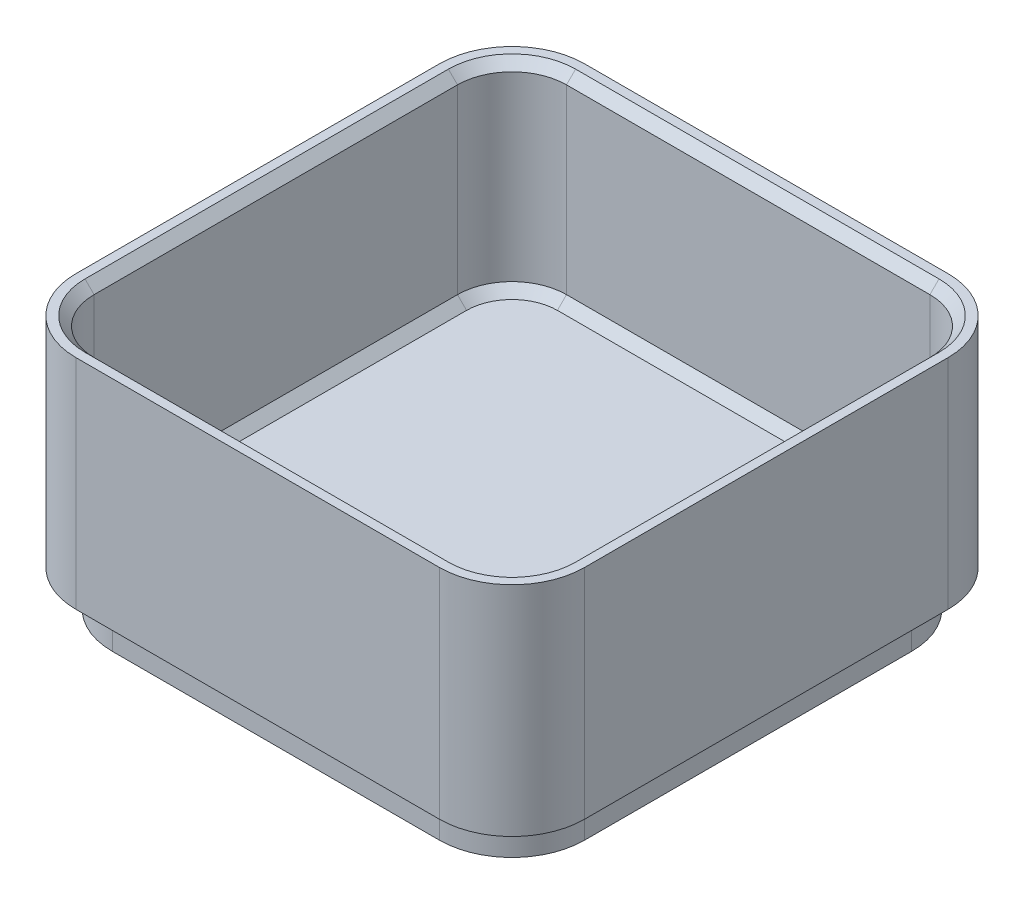
SolidWorks part; units mm, degrees
ref_plane "Front Plane" through (0, 0, 0) normal (0, 0, 1) x (1, 0, 0)
ref_plane "Top Plane" through (0, 0, 0) normal (0, 1, 0) x (1, 0, 0)
ref_plane "Right Plane" through (0, 0, 0) normal (1, 0, 0) x (0, 0, -1)
sketch "Sketch5" plane through (0, 0, 0) normal (0, 1, 0) x (1, 0, 0)
  line L1 (-22.5, -32.5) -> (22.5, -32.5)
  line L2 (-32.5, -22.5) -> (-32.5, 22.5)
  line L3 (-22.5, 32.5) -> (22.5, 32.5)
  line L4 (32.5, -22.5) -> (32.5, 22.5)
  line L5 (-32.5, -32.5) -> (32.5, 32.5) construction
  line L6 (-32.5, 32.5) -> (32.5, -32.5) construction
  arc A0 (-22.5, -32.5) -> (-32.5, -22.5) centre (-22.5, -22.5) cw
  arc A1 (22.5, -32.5) -> (32.5, -22.5) centre (22.5, -22.5) ccw
  arc A2 (22.5, 32.5) -> (32.5, 22.5) centre (22.5, 22.5) cw
  arc A3 (-32.5, 22.5) -> (-22.5, 32.5) centre (-22.5, 22.5) cw
  point P0 (0, 0)
  dimension "D3" = 10
  dimension "D1" = 65
  dimension "D2" = 65
extrude "Boss-Extrude4" add sketch "Sketch5" along normal blind 5
sketch "Sketch6" plane through (0, 5, 0) normal (0, 1, 0) x (1, 0, 0)
  line L1 (35, 35) -> (-35, 35)
  line L2 (35, 35) -> (35, -35)
  line L3 (35, -35) -> (-35, -35)
  line L4 (-35, 35) -> (-35, -35)
  line L5 (35, 35) -> (-35, -35) construction
  line L6 (35, -35) -> (-35, 35) construction
  point P0 (0, 0)
extrude "Boss-Extrude5" add sketch "Sketch6" along normal blind 30
sketch "Sketch8" plane through (0, 0, 0) normal (0, -1, 0) x (1, 0, 0)
  line L0 (-29.5711, 29.5711) -> (-22.5, 22.5)
  arc A0 (-22.5, 32.5) -> (-32.5, 22.5) centre (-22.5, 22.5) ccw construction
  circle A1 centre (-26.0355, 26.0355) radius 3
  circle A2 centre (26.0365, 26.0365) radius 3
  circle A3 centre (26.0375, -26.0355) radius 3
  circle A4 centre (-26.0345, -26.0365) radius 3
  point P8 (0, 0)
  point P15 (0.001, 0.001)
  point P18 (0.002, 0)
  point P21 (0.001, -0.001)
  point P22 (0.001, 0)
  dimension "D1" = 4
extrude "Cut-Extrude1" cut sketch "Sketch8" against normal blind 2 contours A3 | A2 | L0 A1 | L0 A1 | A4
fillet "Fillet1" radius 10 4 edges at (-35, 20, -35) (-35, 20, 35) (35, 20, 35) (35, 20, -35)
sketch "Sketch9" plane through (0, 35, 0) normal (0, 1, 0) x (1, 0, 0)
  line L8 (25, 32.5) -> (-25, 32.5)
  line L9 (-32.5, 25) -> (-32.5, -25)
  line L10 (-25, -32.5) -> (25, -32.5)
  line L11 (32.5, -25) -> (32.5, 25)
  line L12 (25, 32.5) -> (-25, 32.5)
  line L13 (-32.5, 25) -> (-32.5, -25)
  line L14 (-25, -32.5) -> (25, -32.5)
  line L15 (32.5, -25) -> (32.5, 25)
  arc A8 (-25, 32.5) -> (-32.5, 25) centre (-25, 25) ccw
  arc A9 (-32.5, -25) -> (-25, -32.5) centre (-25, -25) ccw
  arc A10 (25, -32.5) -> (32.5, -25) centre (25, -25) ccw
  arc A11 (32.5, 25) -> (25, 32.5) centre (25, 25) ccw
  arc A12 (-25, 32.5) -> (-32.5, 25) centre (-25, 25) ccw
  arc A13 (-32.5, -25) -> (-25, -32.5) centre (-25, -25) ccw
  arc A14 (25, -32.5) -> (32.5, -25) centre (25, -25) ccw
  arc A15 (32.5, 25) -> (25, 32.5) centre (25, 25) ccw
  dimension "D1" = 2.5
extrude "Cut-Extrude2" cut sketch "Sketch9" against normal blind 30
sketch "Sketch10" plane through (0, 5, 0) normal (0, -1, 0) x (1, 0, 0)
  line L8 (-35, 25) -> (-35, -25)
  line L9 (-25, -35) -> (25, -35)
  line L10 (35, -25) -> (35, 25)
  line L11 (25, 35) -> (-25, 35)
  line L12 (-35, 25) -> (-35, -25)
  line L13 (-25, -35) -> (25, -35)
  line L14 (35, -25) -> (35, 25)
  line L15 (25, 35) -> (-25, 35)
  arc A8 (-35, -25) -> (-25, -35) centre (-25, -25) ccw
  arc A9 (25, -35) -> (35, -25) centre (25, -25) ccw
  arc A10 (35, 25) -> (25, 35) centre (25, 25) ccw
  arc A11 (-25, 35) -> (-35, 25) centre (-25, 25) ccw
  arc A12 (-35, -25) -> (-25, -35) centre (-25, -25) ccw
  arc A13 (25, -35) -> (35, -25) centre (25, -25) ccw
  arc A14 (35, 25) -> (25, 35) centre (25, 25) ccw
  arc A15 (-25, 35) -> (-35, 25) centre (-25, 25) ccw
  dimension "D1" = 0
extrude "Boss-Extrude6" add sketch "Sketch10" against normal blind 2.5
chamfer "Chamfer1" distance 1.25 angle 45 16 edges at (32.5, 7.5, 0) (30.3033, 7.5, 30.3033) (0, 7.5, 32.5) (-30.3033, 7.5, 30.3033) (-32.5, 7.5, 0) (-30.3033, 7.5, -30.3033) (0, 7.5, -32.5) (30.3033, 7.5, -30.3033) (-30.3033, 35, 30.3033) (0, 35, 32.5) (-32.5, 35, 0) (30.3033, 35, 30.3033) (-30.3033, 35, -30.3033) (32.5, 35, 0) (0, 35, -32.5) (30.3033, 35, -30.3033)
